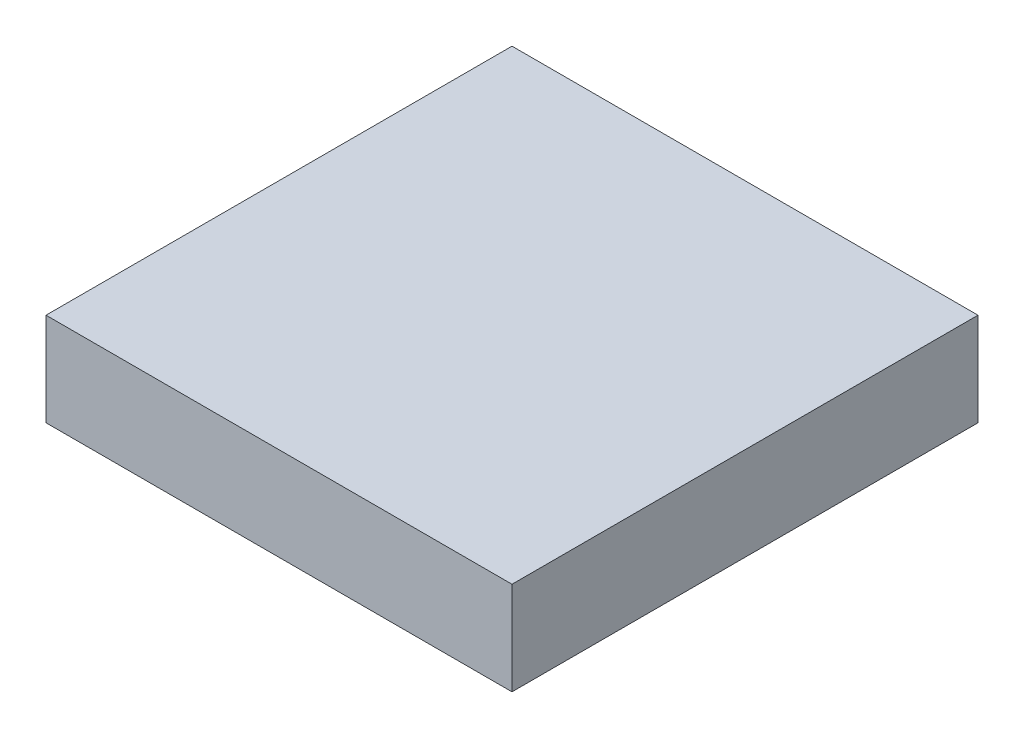
SolidWorks part; units mm, degrees
ref_plane "Front Plane" through (0, 0, 0) normal (0, 0, 1) x (1, 0, 0)
ref_plane "Top Plane" through (0, 0, 0) normal (0, 1, 0) x (1, 0, 0)
ref_plane "Right Plane" through (0, 0, 0) normal (1, 0, 0) x (0, 0, -1)
sketch "Sketch1" plane through (0, 0, 0) normal (0, 1, 0) x (1, 0, 0)
  line L1 (0, 0) -> (16, 0)
  line L2 (0, 0) -> (0, 16)
  line L3 (0, 16) -> (16, 16)
  line L4 (16, 0) -> (16, 16)
  dimension "D1" = 16
  dimension "D2" = 16
extrude "Boss-Extrude1" add sketch "Sketch1" along normal blind 3.2
shell "Shell1" thickness 1.6
